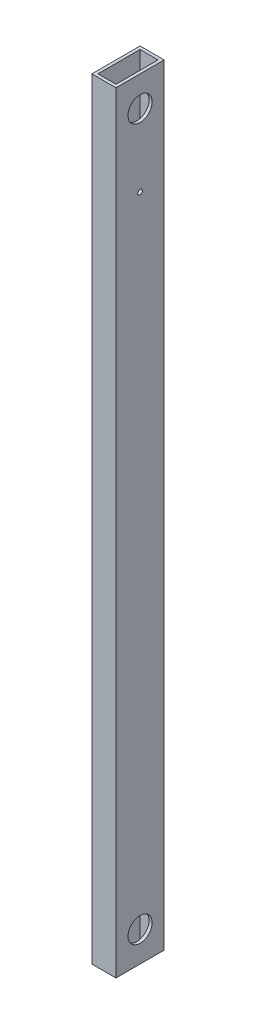
SolidWorks part; units mm, degrees
material "6061-T6 (SS)"
ref_plane "Front Plane" through (0, 0, 0) normal (0, 0, 1) x (1, 0, 0)
ref_plane "Top Plane" through (0, 0, 0) normal (0, 1, 0) x (1, 0, 0)
ref_plane "Right Plane" through (0, 0, 0) normal (1, 0, 0) x (0, 0, -1)
sketch "Sketch1" plane through (0, 0, 0) normal (0, 1, 0) x (1, 0, 0)
  line L1 (0, 0) -> (25.4, 0)
  line L2 (0, 0) -> (0, 50.8)
  line L3 (0, 50.8) -> (25.4, 50.8)
  line L4 (25.4, 0) -> (25.4, 50.8)
  dimension "D1" = 50.8
  dimension "D2" = 25.4
extrude "Boss-Extrude1" add sketch "Sketch1" along normal mid plane 812.8
shell "Shell1" thickness 3.175
sketch "Sketch2" plane through (25.4, 0, 0) normal (1, 0, 0) x (0, 0, -1)
  line L0 (25.4, -374.65) -> (25.4, 374.65) construction
  line L1 (0, 406.4) -> (50.8, 406.4) construction
  line L2 (0, -406.4) -> (50.8, -406.4) construction
  circle A0 centre (25.4, 374.65) radius 12.7
  circle A1 centre (25.4, -374.65) radius 12.7
  circle A2 centre (25.4, 298.45) radius 2.4892
  dimension "D2" = 25.4
  dimension "D3" = 31.75
  dimension "D4" = 31.75
  dimension "D5" = 4.9784
  dimension "D1" = 25.4
  dimension "D6" = 76.2
extrude "Cut-Extrude1" cut sketch "Sketch2" against normal through all
